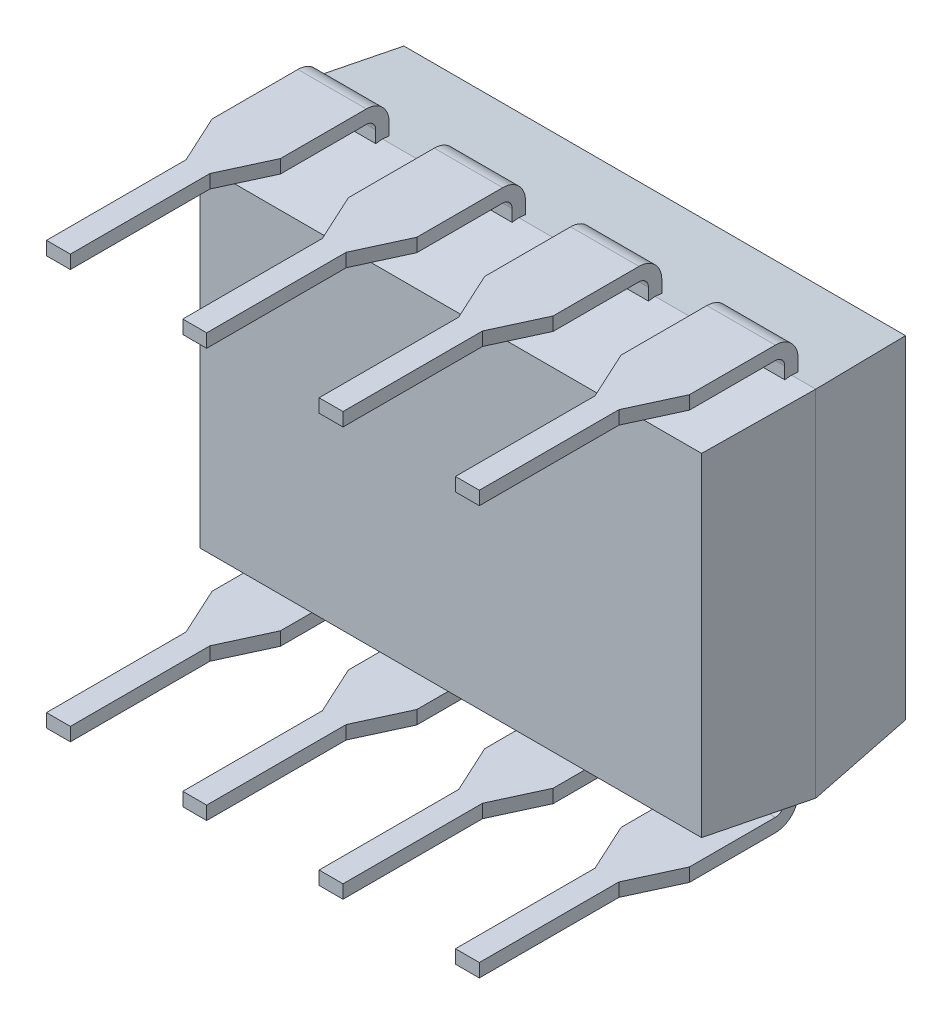
SolidWorks part; units mm, degrees
ref_plane "Plano frontal" through (0, 0, 0) normal (0, 0, 1) x (1, 0, 0)
ref_plane "Plano superior" through (0, 0, 0) normal (0, 1, 0) x (1, 0, 0)
ref_plane "Plano direito" through (0, 0, 0) normal (1, 0, 0) x (0, 0, -1)
sketch "Esboço1" plane through (0, 0, 0) normal (1, 0, 0) x (0, 0, -1)
  line L0 (0.9, 3.1) -> (0.9, -3.1)
  line L1 (0.9, -3.1) -> (2.8, -3.3)
  line L2 (2.8, -3.3) -> (4.7, -3.1)
  line L3 (4.7, -3.1) -> (4.7, 3.1)
  line L4 (4.7, 3.1) -> (2.8, 3.3)
  line L5 (2.8, 3.3) -> (0.9, 3.1)
  line L6 (2.8, 3.3) -> (2.8, -3.3) construction
  line L7 (4.7, 0) -> (2.8, 0) construction
  line L8 (2.8, 0) -> (0.9, 0) construction
  line L9 (0.9, 0) -> (0, 0) construction
  dimension "D1" = 6.6
  dimension "D2" = 6.2
  dimension "D3" = 3.8
  dimension "D4" = 0.9
extrude "Ressalto-extrusão1" add sketch "Esboço1" along normal mid plane 9.8
sketch "Esboço3" plane through (0, 0, 0) normal (0, 1, 0) x (1, 0, 0)
  line L0 (-4.9, 2.8) -> (-4.6699, 4.7268)
  line L1 (-4.6699, 4.7268) -> (-5.8363, 4.7268)
  line L2 (-5.8363, 4.7268) -> (-5.8363, 0.8732)
  line L3 (-5.8363, 0.8732) -> (-4.6699, 0.8732)
  line L4 (-4.6699, 0.8732) -> (-4.9, 2.8)
  line L5 (-5.8363, 2.8) -> (-4.9, 2.8) construction
  line L6 (-4.9, 0.9) -> (-4.9, 2.8) construction
  dimension "D1" = 6.81
  dimension "D2" = 3.8537
  dimension "D3" = 1.1665
extrude "Corte-extrusão2" cut sketch "Esboço3" against normal mid plane 7.1
mirror "Espelhar1" about plane through (0, 0, 0) normal (1, 0, 0) of "Corte-extrusão2"
sketch "Esboço8" plane through (0, 0, -4.7) normal (0, 0, -1) x (-1, 0, 0)
  line L0 (4.6731, -3.1) -> (4.6731, 3.1) construction
  circle A0 centre (4.6731, 0) radius 1
  dimension "D1" = 2
extrude "Corte-extrusão5" cut sketch "Esboço8" against normal blind 0.5
ref_plane "Plano1" through (0, 3.3, 0) normal (0, 1, 0) x (1, 0, 0)
sketch "Esboço6" plane through (0, 3.3, 0) normal (0, 1, 0) x (1, 0, 0)
  line L0 (-3.1725, 2.8) -> (0, 2.8) construction
  line L1 (-4.4475, 2.925) -> (-3.1725, 2.925)
  line L2 (-4.4475, 2.925) -> (-4.4475, 2.675)
  line L3 (-4.4475, 2.675) -> (-3.1725, 2.675)
  line L4 (-3.1725, 2.925) -> (-3.1725, 2.675)
  line L5 (4.9, 2.8) -> (-4.9, 2.8) construction
  line L6 (-3.81, 2.925) -> (-3.81, 2.675) construction
  dimension "D1" = 0.25
  dimension "D2" = 1.275
  dimension "D3" = 1.09
extrude "Ressalto-extrusão2" add sketch "Esboço6" along normal mid plane 0.05
sketch "Esboço7" plane through (0, 3.325, 0) normal (0, 1, 0) x (1, 0, 0)
  line L0 (-4.4475, 2.925) -> (-4.4475, 2.675) construction
  line L1 (-3.1725, 2.925) -> (-4.4475, 2.925) construction
  line L2 (-3.1725, 2.675) -> (-3.1725, 2.925) construction
  line L3 (-4.4475, 2.675) -> (-3.1725, 2.675) construction
  line L4 (-4.4475, 2.925) -> (-4.4475, 2.675)
  line L5 (-3.1725, 2.925) -> (-4.4475, 2.925)
  line L6 (-3.1725, 2.675) -> (-3.1725, 2.925)
  line L7 (-4.4475, 2.675) -> (-3.1725, 2.675)
  line L8 (-4.4475, 2.8) -> (-3.1725, 2.8) construction
sketch3d "3DSketch1"
  line L0 (-3.81, 3.325, -2.8) -> (-3.81, 3.51, -2.8)
  line L1 (-3.81, 3.325, -2.8) -> (-3.81, 0, -2.8) construction
  line L2 (-4.4475, 3.325, -2.8) -> (-3.1725, 3.325, -2.8) construction
  line L3 (-3.81, 3.81, -2.5) -> (-3.81, 3.81, 0)
  line L4 (-3.81, 0, -2.8) -> (0, 0, 0) construction
  arc A0 (-3.81, 3.51, -2.8) -> (-3.81, 3.81, -2.5) centre (-3.81, 3.51, -2.5) ccw
  point P5 (-3.51, 3.51, -2.5)
  dimension "D3" = 0.3
  dimension "D1" = 2.8
  dimension "D2" = 3.81
sweep "Varredura1" add profiles "Esboço7" path "3DSketch1"
sketch "Esboço9" plane through (0, 3.935, 0) normal (0, 1, 0) x (1, 0, 0)
  line L0 (-4.0325, 0) -> (-4.4475, 0.9)
  line L1 (-3.1725, 0) -> (-4.4475, 0) construction
  line L3 (-4.4475, 2.5) -> (-4.4475, 0) construction
  line L4 (-4.4475, 0.9) -> (-4.4475, -0.2)
  line L5 (-4.4475, -0.2) -> (-3.1725, -0.2)
  line L6 (-3.1725, -0.2) -> (-3.1725, 0.9)
  line L7 (-3.1725, 2.5) -> (-3.1725, 0) construction
  line L8 (-3.1725, 0.9) -> (-3.5875, 0)
  line L9 (-3.5875, 0) -> (-4.0325, 0)
  line L10 (-3.81, 0) -> (-3.81, 2.5) construction
  line L11 (-3.1725, 2.5) -> (-4.4475, 2.5) construction
  dimension "D1" = 0.9
  dimension "D2" = 0.445
  dimension "D3" = 0.2
extrude "Corte-extrusão6" cut sketch "Esboço9" against normal up to next
sketch "Esboço10" plane through (0, 0, 0) normal (0, 0, 1) x (1, 0, 0)
  line L0 (-3.5875, 3.935) -> (-4.0325, 3.935) construction
  line L1 (-4.0325, 3.935) -> (-4.0325, 3.685) construction
  line L2 (-4.0325, 3.685) -> (-3.5875, 3.685) construction
  line L3 (-3.5875, 3.685) -> (-3.5875, 3.935) construction
  line L4 (-3.5875, 3.935) -> (-4.0325, 3.935)
  line L5 (-4.0325, 3.935) -> (-4.0325, 3.685)
  line L6 (-4.0325, 3.685) -> (-3.5875, 3.685)
  line L7 (-3.5875, 3.685) -> (-3.5875, 3.935)
extrude "Ressalto-extrusão3" add sketch "Esboço10" along normal blind 2.6
mirror "Espelhar2" about plane through (0, 0, 0) normal (0, 1, 0) of "Ressalto-extrusão3", "Corte-extrusão6", "Varredura1", "Ressalto-extrusão2"
pattern_linear "Padrão linear1" count 4 spacing 2.54 along (1, 0, 0) of "Ressalto-extrusão2", "Varredura1", "Corte-extrusão6", "Ressalto-extrusão3", "Espelhar2"
